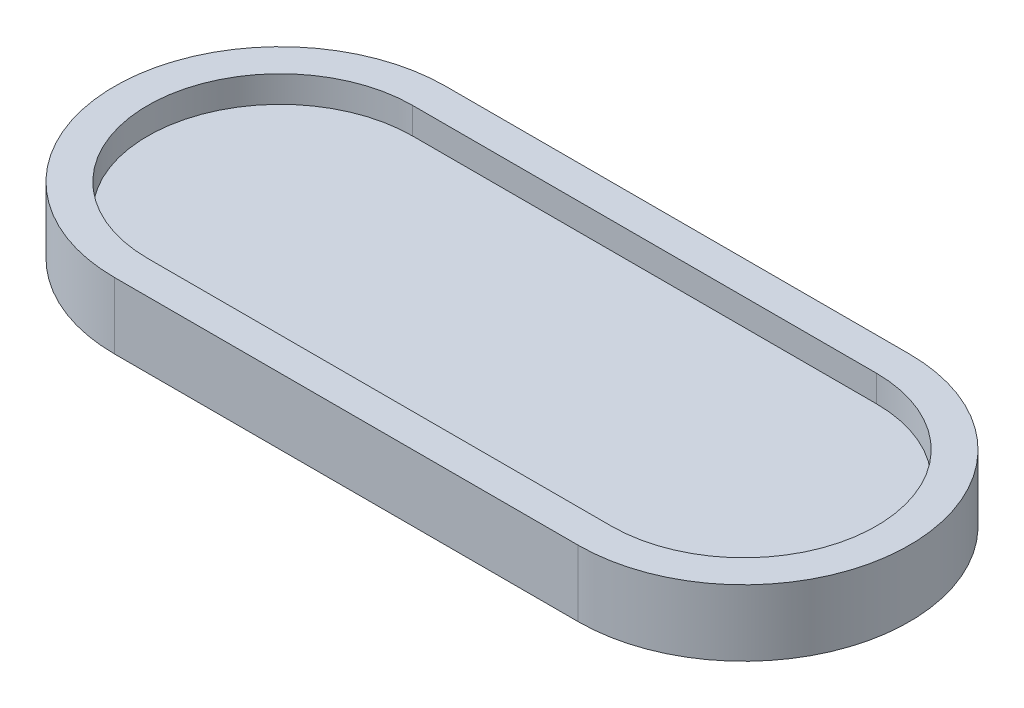
SolidWorks part; units mm, degrees
ref_plane "前基準面" through (0, 0, 0) normal (0, 0, 1) x (1, 0, 0)
ref_plane "上基準面" through (0, 0, 0) normal (0, 1, 0) x (1, 0, 0)
ref_plane "右基準面" through (0, 0, 0) normal (1, 0, 0) x (0, 0, -1)
sketch "草圖1" plane through (0, 0, 0) normal (0, 1, 0) x (1, 0, 0)
  line L0 (0, 0) -> (35, 0) construction
  line L1 (0, 12.5) -> (35, 12.5)
  line L2 (0, -12.5) -> (35, -12.5)
  line L3 (47.5, 0) -> (47.5, 23.3491) construction
  line L4 (-12.5, 0) -> (-12.5, 27.7516) construction
  arc A0 (0, 12.5) -> (0, -12.5) centre (0, 0) ccw
  arc A1 (35, -12.5) -> (35, 12.5) centre (35, 0) ccw
  point P3 (17.5, 0)
  dimension "D1" = 12.5
  dimension "D2" = 60
extrude "填料-伸長1" add sketch "草圖1" along normal blind 5
sketch "草圖2" plane through (0, 5, 0) normal (0, 1, 0) x (1, 0, 0)
  line L4 (0, -10) -> (35, -10)
  line L5 (35, 10) -> (0, 10)
  line L6 (0, -10) -> (35, -10)
  line L7 (35, 10) -> (0, 10)
  arc A4 (0, 10) -> (0, -10) centre (0, 0) ccw
  arc A5 (35, -10) -> (35, 10) centre (35, 0) ccw
  arc A6 (0, 10) -> (0, -10) centre (0, 0) ccw
  arc A7 (35, -10) -> (35, 10) centre (35, 0) ccw
  dimension "D1" = 2.5
extrude "除料-伸長1" cut sketch "草圖2" against normal blind 2
